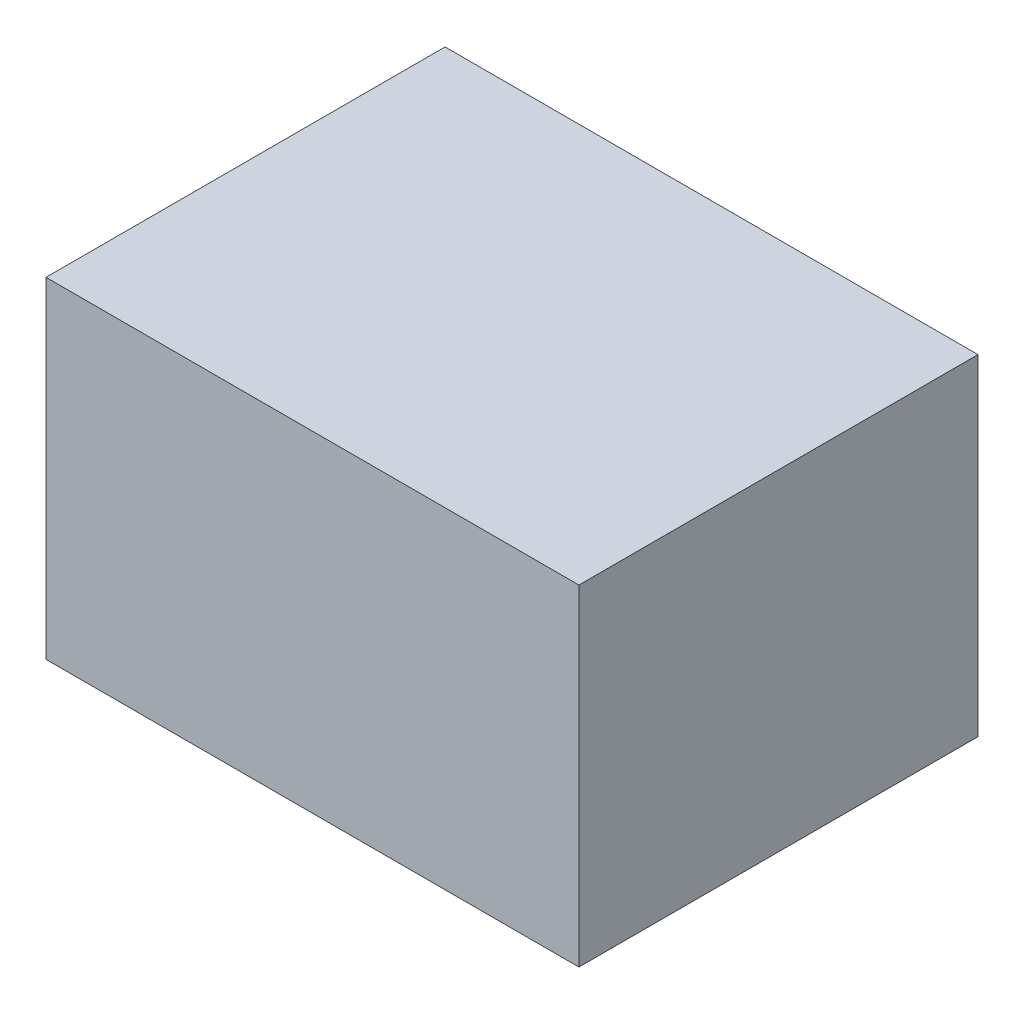
SolidWorks part; units mm, degrees
ref_plane "Front Plane" through (0, 0, 0) normal (0, 0, 1) x (1, 0, 0)
ref_plane "Top Plane" through (0, 0, 0) normal (0, 1, 0) x (1, 0, 0)
ref_plane "Right Plane" through (0, 0, 0) normal (1, 0, 0) x (0, 0, -1)
sketch "Sketch1" plane through (0, 0, 0) normal (0, 0, 1) x (1, 0, 0)
  line L1 (0, 0) -> (21.1, 0)
  line L2 (0, 0) -> (0, 13.1)
  line L3 (0, 13.1) -> (21.1, 13.1)
  line L4 (21.1, 0) -> (21.1, 13.1)
  dimension "D1" = 13.1
  dimension "D2" = 21.1
extrude "Boss-Extrude1" add sketch "Sketch1" along normal blind 15.8
